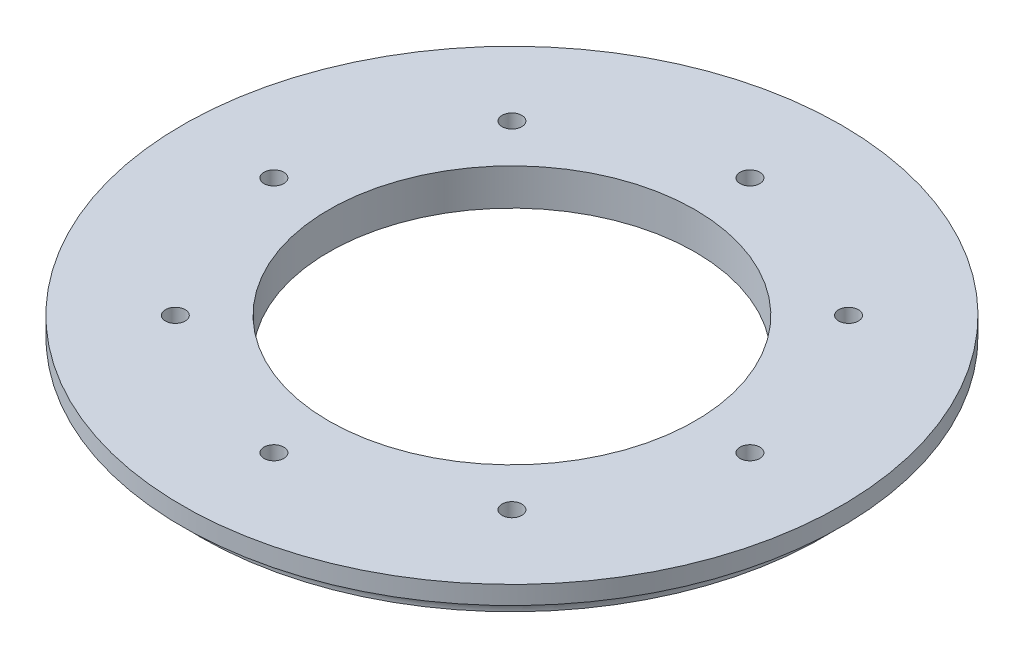
SolidWorks part; units mm, degrees
ref_plane "Front Plane" through (0, 0, 0) normal (0, 0, 1) x (1, 0, 0)
ref_plane "Top Plane" through (0, 0, 0) normal (0, 1, 0) x (1, 0, 0)
ref_plane "Right Plane" through (0, 0, 0) normal (1, 0, 0) x (0, 0, -1)
sketch "Sketch1" plane through (0, 0, 0) normal (0, 0, 1) x (1, 0, 0)
  line L0 (0, 0) -> (0, 36.9486) construction
  line L1 (0, 0) -> (-45, 0)
  line L2 (0, 0) -> (0, 5)
  line L3 (0, 5) -> (-45, 5)
  line L4 (-45, 0) -> (-45, 5)
  line L5 (0, 0) -> (-45, 5) construction
  line L6 (0, 5) -> (-45, 0) construction
  arc A0 (-42.5, 0) -> (-45, 2.5) centre (-45, 0) ccw
  point P0 (-22.5, 2.5)
  dimension "ball_track" = 5
  dimension "slew_radius" = 45
  dimension "D2" = 5
revolve "Revolve1" add sketch "Sketch1" angle 360 about L0
ref_plane "ball center plane" through (0, 0, 0) normal (0, 1, 0) x (1, 0, 0)
sketch "Sketch2" plane through (0, 5, 0) normal (0, 1, 0) x (1, 0, 0)
  circle A0 centre (0, 0) radius 32.5 construction
  circle A1 centre (0, 32.5) radius 1.35
  circle A2 centre (22.981, 22.981) radius 1.35
  circle A3 centre (32.5, 0) radius 1.35
  circle A4 centre (22.981, -22.981) radius 1.35
  circle A5 centre (0, -32.5) radius 1.35
  circle A6 centre (-22.981, -22.981) radius 1.35
  circle A7 centre (-32.5, 0) radius 1.35
  circle A8 centre (-22.981, 22.981) radius 1.35
  point P21 (0, 0)
  dimension "D1" = 65
  dimension "D2" = 2.7
  dimension "D3" = 8
extrude "Cut-Extrude1" cut sketch "Sketch2" against normal through all
sketch "Sketch4" plane through (0, 5, 0) normal (0, 1, 0) x (1, 0, 0)
  circle A0 centre (0, 0) radius 25 construction
  circle A1 centre (0, 0) radius 25
extrude "Cut-Extrude2" cut sketch "Sketch4" against normal through all
equation "\"test\"= 1cm"
equation "\"slew_radius\"=5"
equation "\"ball_diameter\"=0.5"
